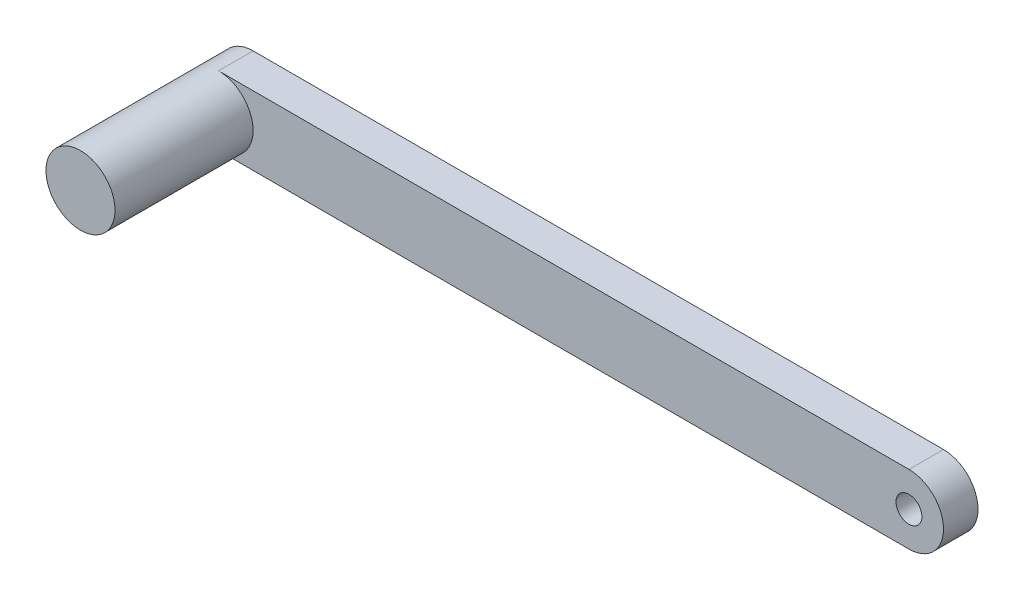
SolidWorks part; units mm, degrees
ref_plane "Front Plane" through (0, 0, 0) normal (0, 0, 1) x (1, 0, 0)
ref_plane "Top Plane" through (0, 0, 0) normal (0, 1, 0) x (1, 0, 0)
ref_plane "Right Plane" through (0, 0, 0) normal (1, 0, 0) x (0, 0, -1)
sketch "Sketch1" plane through (0, 0, 0) normal (0, 0, 1) x (1, 0, 0)
  line L0 (0, -2) -> (40, -2)
  line L1 (0, 2) -> (40, 2)
  arc A0 (0, 2) -> (0, -2) centre (0, 0) ccw
  arc A1 (40, -2) -> (40, 2) centre (40, 0) ccw
  dimension "D2" = 4
  dimension "D3" = 4
  dimension "D1" = 40
extrude "Boss-Extrude1" add sketch "Sketch1" along normal blind 2
sketch "Sketch2" plane through (0, 0, 2) normal (0, 0, 1) x (1, 0, 0)
  circle A0 centre (0, 0) radius 2
  dimension "D1" = 4
extrude "Boss-Extrude2" add sketch "Sketch2" along normal blind 8
sketch "Croquis1" plane through (0, 0, 2) normal (0, 0, 1) x (1, 0, 0)
  circle A0 centre (40, 0) radius 0.75
  dimension "D1" = 1.5
extrude "Cortar-Extruir1" cut sketch "Croquis1" against normal blind 10
